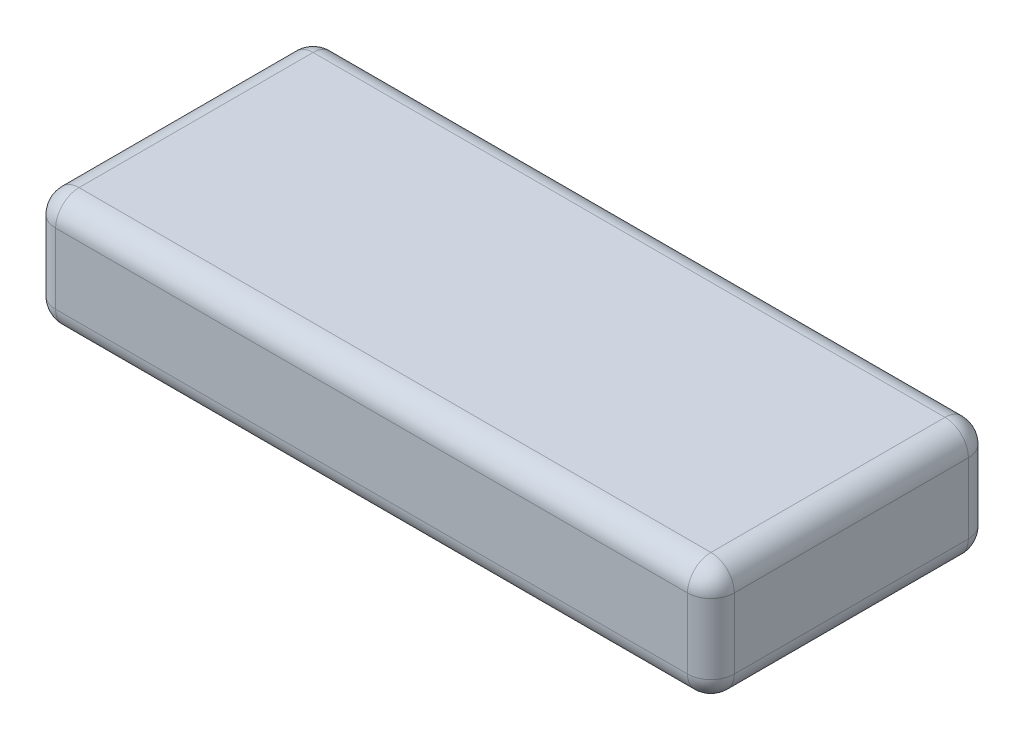
SolidWorks part; units mm, degrees
ref_plane "Front Plane" through (0, 0, 0) normal (0, 0, 1) x (1, 0, 0)
ref_plane "Top Plane" through (0, 0, 0) normal (0, 1, 0) x (1, 0, 0)
ref_plane "Right Plane" through (0, 0, 0) normal (1, 0, 0) x (0, 0, -1)
sketch "Sketch1" plane through (0, 0, 0) normal (0, 1, 0) x (1, 0, 0)
  line L1 (-14.5, -6) -> (14.5, -6)
  line L2 (-14.5, -6) -> (-14.5, 6)
  line L3 (-14.5, 6) -> (14.5, 6)
  line L4 (14.5, -6) -> (14.5, 6)
  line L5 (-14.5, -6) -> (14.5, 6) construction
  line L6 (-14.5, 6) -> (14.5, -6) construction
  point P0 (0, 0)
  dimension "D1" = 29
  dimension "D2" = 12
extrude "Boss-Extrude1" add sketch "Sketch1" along normal blind 5
fillet "Fillet1" radius 1 12 edges at (-14.5, 2.5, -6) (-14.5, 2.5, 6) (14.5, 2.5, 6) (14.5, 2.5, -6) (0, 0, -6) (-14.5, 0, 0) (0, 0, 6) (14.5, 0, 0) (0, 5, 6) (-14.5, 5, 0) (0, 5, -6) (14.5, 5, 0)
